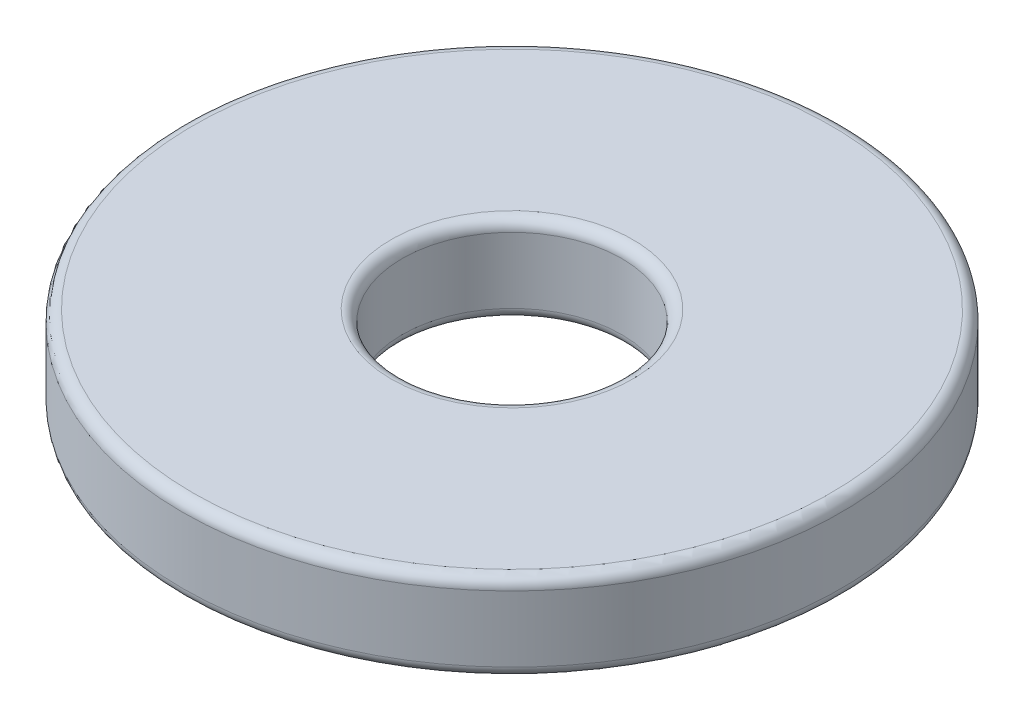
SolidWorks part; units mm, degrees
material "6061-T6 (SS)"
ref_plane "Front Plane" through (0, 0, 0) normal (0, 0, 1) x (1, 0, 0)
ref_plane "Top Plane" through (0, 0, 0) normal (0, 1, 0) x (1, 0, 0)
ref_plane "Right Plane" through (0, 0, 0) normal (1, 0, 0) x (0, 0, -1)
sketch "Sketch1" plane through (0, 0, 0) normal (0, 1, 0) x (1, 0, 0)
  circle A0 centre (0, 0) radius 2.5
  circle A1 centre (0, 0) radius 7.5
  dimension "D1" = 5
  dimension "D2" = 15
extrude "Boss-Extrude1" add sketch "Sketch1" along normal blind 2
fillet "Fillet1" radius 0.25 4 edges at (0, 0, 2.5) (0, 0, 7.5) (0, 2, 2.5) (0, 2, 7.5)
